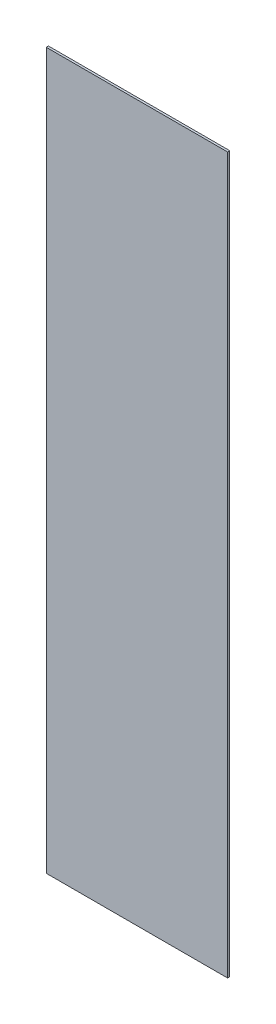
SolidWorks part; units mm, degrees
material "7075-O (SS)"
ref_plane "Front Plane" through (0, 0, 0) normal (0, 0, 1) x (1, 0, 0)
ref_plane "Top Plane" through (0, 0, 0) normal (0, 1, 0) x (1, 0, 0)
ref_plane "Right Plane" through (0, 0, 0) normal (1, 0, 0) x (0, 0, -1)
sketch "Sketch1" plane through (0, 0, 0) normal (0, 0, 1) x (1, 0, 0)
  line L1 (0, 0) -> (83, 0)
  line L2 (0, 0) -> (0, 327.5)
  line L3 (0, 327.5) -> (83, 327.5)
  line L4 (83, 0) -> (83, 327.5)
  dimension "D1" = 327.5
  dimension "D2" = 83
extrude "Boss-Extrude1" add sketch "Sketch1" along normal blind 1
